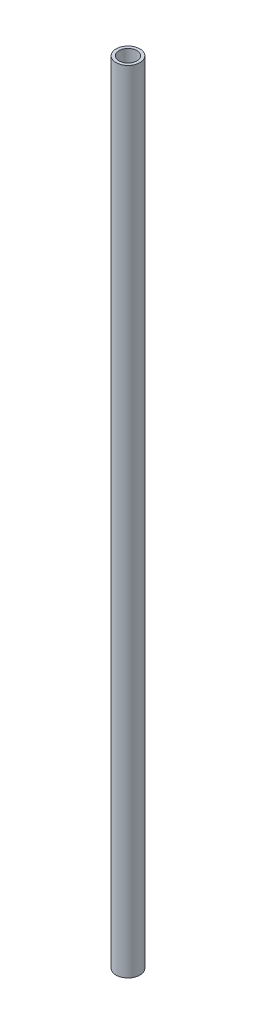
SolidWorks part; units mm, degrees
material "Thornel Mat VMA"
ref_plane "前视基准面" through (0, 0, 0) normal (0, 0, 1) x (1, 0, 0)
ref_plane "上视基准面" through (0, 0, 0) normal (0, 1, 0) x (1, 0, 0)
ref_plane "右视基准面" through (0, 0, 0) normal (1, 0, 0) x (0, 0, -1)
sketch "草图1" plane through (0, 0, 0) normal (0, 1, 0) x (1, 0, 0)
  circle A0 centre (0, 0) radius 4
  circle A1 centre (0, 0) radius 3
  dimension "D1" = 8
  dimension "D2" = 1
extrude "凸台-拉伸1" add sketch "草图1" along normal blind 265
